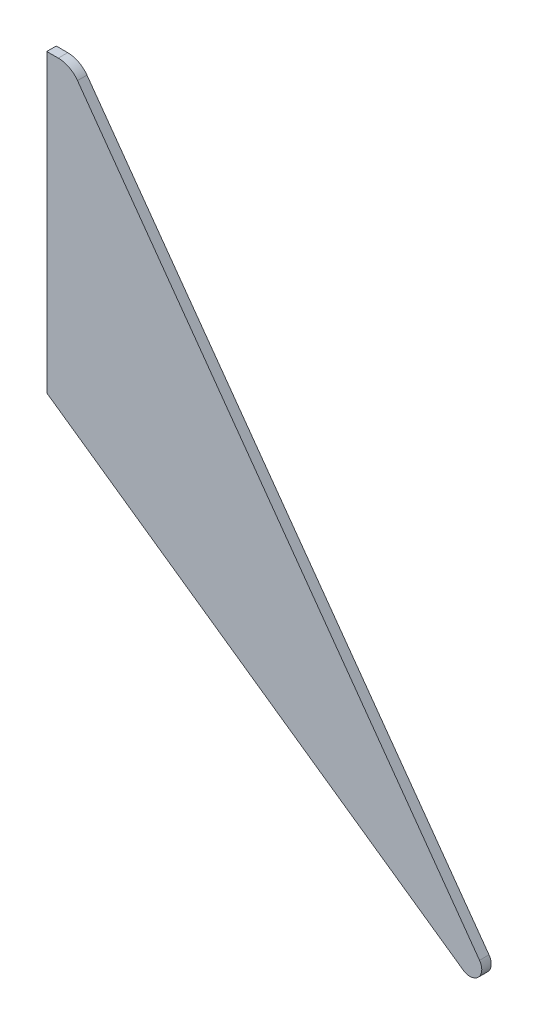
SolidWorks part; units mm, degrees
material "AISI 304"
ref_plane "Спереди" through (0, 0, 0) normal (0, 0, 1) x (1, 0, 0)
ref_plane "Сверху" through (0, 0, 0) normal (0, 1, 0) x (1, 0, 0)
ref_plane "Справа" through (0, 0, 0) normal (1, 0, 0) x (0, 0, -1)
sketch "Эскиз1" plane through (0, 0, 0) normal (0, 0, 1) x (1, 0, 0)
  line L0 (0, 0) -> (0, 125)
  line L1 (0, 125) -> (10, 125)
  line L2 (10, 125) -> (200, -140.0415)
  line L3 (200, -140.0415) -> (0, 0)
  line L4 (0, 0) -> (0, -72.6923) construction
  dimension "D1" = 125
  dimension "D2" = 10
  dimension "D3" = 55
  dimension "D4" = 200
extrude "Бобышка-Вытянуть1" add sketch "Эскиз1" along normal blind 4
fillet "Скругление1" radius 5 1 edges at (200, -140.0415, 2)
fillet "Скругление2" radius 10 1 edges at (10, 125, 2)
